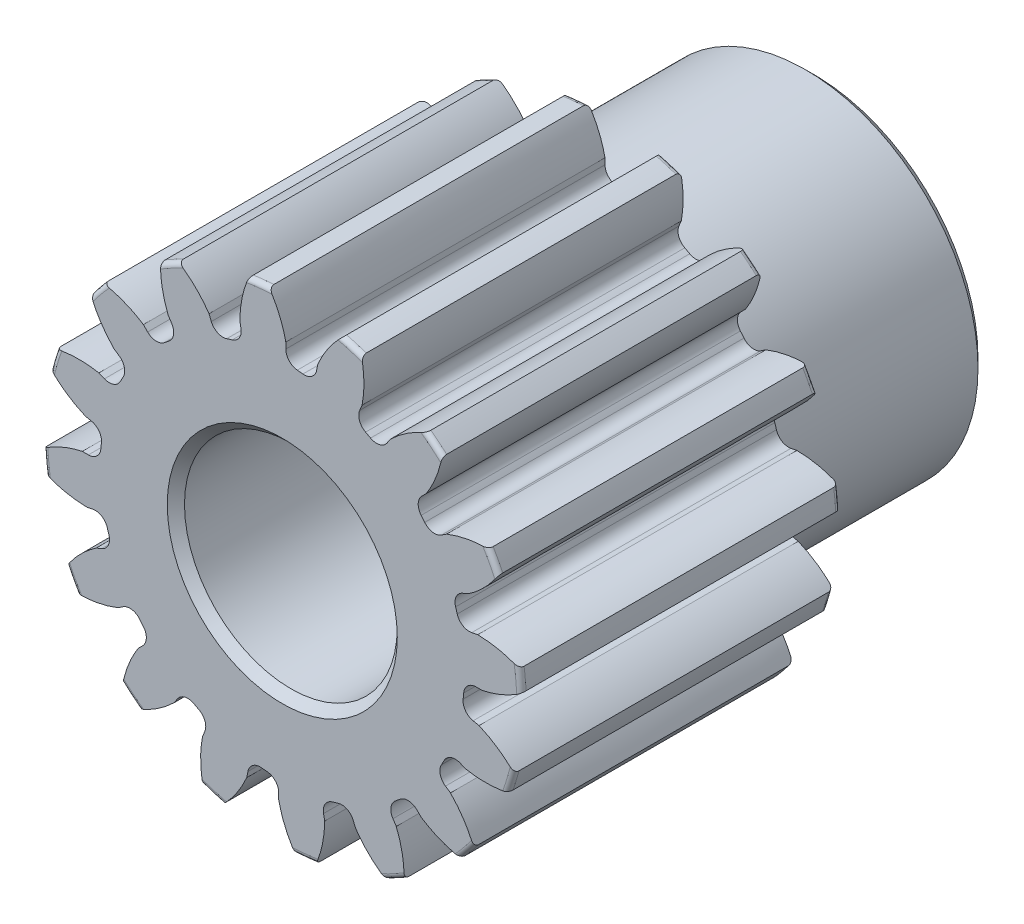
SolidWorks part; units mm, degrees
ref_plane "Front" through (0, 0, 0) normal (0, 0, 1) x (1, 0, 0)
ref_plane "Top" through (0, 0, 0) normal (0, 1, 0) x (1, 0, 0)
ref_plane "Right" through (0, 0, 0) normal (1, 0, 0) x (0, 0, -1)
sketch "Sketch1" plane through (0, 0, 0) normal (0, 0, 1) x (1, 0, 0)
  line L0 (-203.2, 0) -> (203.2, 0) construction
  circle A0 centre (0, 0) radius 14.2875
  circle A1 centre (0, 0) radius 12.7 construction
  circle A3 centre (0, 0) radius 10.8633 construction
  dimension "D1" = 1.8367
  dimension "OD" = 28.575
  dimension "Ptich Dia" = 25.4
  dimension "D2" = 3.4242
  dimension "Root Dia" = 21.7265
  dimension "D3" = 1.5875
  dimension "Number of Teeth" = 406.4
extrude "Boss-Extrude1" add sketch "Sketch1" against normal blind 19.05
sketch "Sketch2" plane through (0, 0, 0) normal (1, 0, 0) x (0, 0, -1)
  line L0 (19.05, 0) -> (31.75, 0)
  line L1 (19.05, 0) -> (19.05, 10.287)
  line L2 (19.05, 10.287) -> (31.75, 10.287)
  line L3 (31.75, 10.287) -> (31.75, 0)
  point P5 (31.75, -10.287)
  point P6 (0, -14.2875)
  point P7 (19.05, -14.2875)
  point P9 (0, 14.2875)
  dimension "Face Wd" = 19.05
  dimension "B Hub Dia" = 20.574
  dimension "D O'all Lg." = 31.75
revolve "Revolve1" add sketch "Sketch2" angle 360 about L0
fillet "Fillet2" radius 0.2858 3 edges at (14.2875, 0, -19.05) (14.2875, 0, 0) (10.287, 0, -19.05)
sketch "Sketch3" plane through (0, 0, 0) normal (0, 0, 1) x (1, 0, 0)
  line L0 (0, 0) -> (0, 14.2875) construction
  line L1 (-4.0817, 11.2144) -> (0, 12.7)
  line L2 (-9.5921, 12.7) -> (9.5921, 12.7) construction
  line L3 (-9.0136, 9.4193) -> (9.0136, 15.9807) construction
  line L4 (-4.0817, 11.2144) -> (0, 0) construction
  line L5 (-9.951, 6.5878) -> (0, 0) construction
  line L6 (-9.951, 6.5878) -> (-3.3571, 16.548) construction
  line L7 (-2.8353, 11.5924) -> (0, 0) construction
  line L8 (-2.8353, 11.5924) -> (0.1182, 12.3148) construction
  arc A0 (-4.0817, 11.2144) -> (-9.951, 6.5878) centre (0, 0) ccw
  circle A1 centre (0, 0) radius 12.7 construction
  circle A2 centre (0, 0) radius 11.9341 construction
  arc A3 (-4.0817, 11.2144) -> (-2.8353, 11.5924) centre (0, 0) cw
  circle A4 centre (0, 0) radius 14.2875 construction
  point P6 (0, 12.7)
  dimension "D1" = 4.3437
  dimension "Pressure Angle" = 20
  dimension "D2" = 7.6014
  dimension "D3" = 11.9451
  dimension "D4" = 1.3031
  dimension "D5" = 3.0406
sketch "Sketch4" plane through (0, 0, 0) normal (0, 0, 1) x (1, 0, 0)
  line L0 (0, 0) -> (1.2388, 12.578) construction
  line L1 (0.2108, 11.9322) -> (0.2108, 10.8612)
  line L2 (0, 12.7) -> (2.4777, 12.456) construction
  line L3 (2.1211, 11.7441) -> (1.9122, 10.6937)
  line L4 (0.2108, 10.8612) -> (0, 0) construction
  line L5 (0, 0) -> (0, 14.2875) construction
  line L6 (-9.951, 6.5878) -> (-3.3571, 16.548) construction
  line L7 (-9.951, 6.5878) -> (-3.3571, 16.548) construction
  arc A0 (1.9122, 10.6937) -> (0.2108, 10.8612) centre (0, 0) ccw
  arc A1 (0, 12.7) -> (2.4777, 12.456) centre (0, 0) cw construction
  circle A2 centre (0, 0) radius 12.7 construction
  circle A3 centre (0, 0) radius 11.9341 construction
  circle A4 centre (0, 0) radius 10.8633 construction
  arc A5 (6.521, 15.5751) -> (-3.3571, 16.548) centre (0, 0) ccw
  spline S0 degree 2 poles (-3.3571, 16.548) (-0.4015, 14.8243) (0.2108, 11.9322) knots 0 0 0 1 1 1
  spline S1 degree 2 poles (6.521, 15.5751) (3.2858, 14.4611) (2.1211, 11.7441) knots 0 0 0 1 1 1
  dimension "D1" = 2.4936
extrude "Cut-Extrude1" cut sketch "Sketch4" against normal through all
fillet "Fillet1" radius 0.7481 2 edges at (1.9122, 10.6937, -9.525) (0.2108, 10.8612, -9.525)
pattern_circular "CirPattern1" count 16 over 360 about axis through (0, 0, -19.05) along (0, 0, 1) of "Cut-Extrude1", "Fillet1"
sketch "Sketch5" plane through (0, 0, 0) normal (0, 0, 1) x (1, 0, 0)
  circle A0 centre (0, 0) radius 6.35
  circle A1 centre (0, 0) radius 6.35 construction
  dimension "Bore Min" = 12.7
  dimension "Bore Max" = 12.7
extrude "Cut-Extrude2" cut sketch "Sketch5" against normal through all
chamfer "Chamfer1" distance 0.5144 angle 45 3 edges at (10.287, 0, -31.75) (6.35, 0, 0) (6.35, 0, -31.75)
sketch "Pitch Dia" plane through (0, 0, 0) normal (0, 0, 1) x (1, 0, 0)
  circle A0 centre (0, 0) radius 12.7 construction
  circle A1 centre (0, 0) radius 12.7 construction
equation "\"D1@Boss-Extrude1\" = \"Face Wd@Sketch2\""
equation "\"D2@Sketch3\" = \"D1@Sketch3\"*1.75"
equation "\"D3@Sketch3\" = \"D1@Sketch3\"+\"D2@Sketch3\""
equation "\"D4@Sketch3\" = \"D1@Sketch3\"*.3"
equation "\"D5@Sketch3\" = \"D1@Sketch3\"-\"D4@Sketch3\""
equation "\"D1@Sketch4\" = 1.5708/(\"Number of Teeth@Sketch1\"/\"Ptich Dia@Sketch1\")"
equation "\"D1@Chamfer1\" = \"B Hub Dia@Sketch2\"*.025"
equation "\"D1@CirPattern1\" = \"Number of Teeth@Sketch1\""
equation "\"D1@Fillet1\" = \"D1@Sketch4\"*.3"
equation "\"D1@Fillet2\" = \"OD@Sketch1\"*.01"
equation "\"D1@Sketch1\" = 1.157/(\"Number of Teeth@Sketch1\"/\"Ptich Dia@Sketch1\")"
